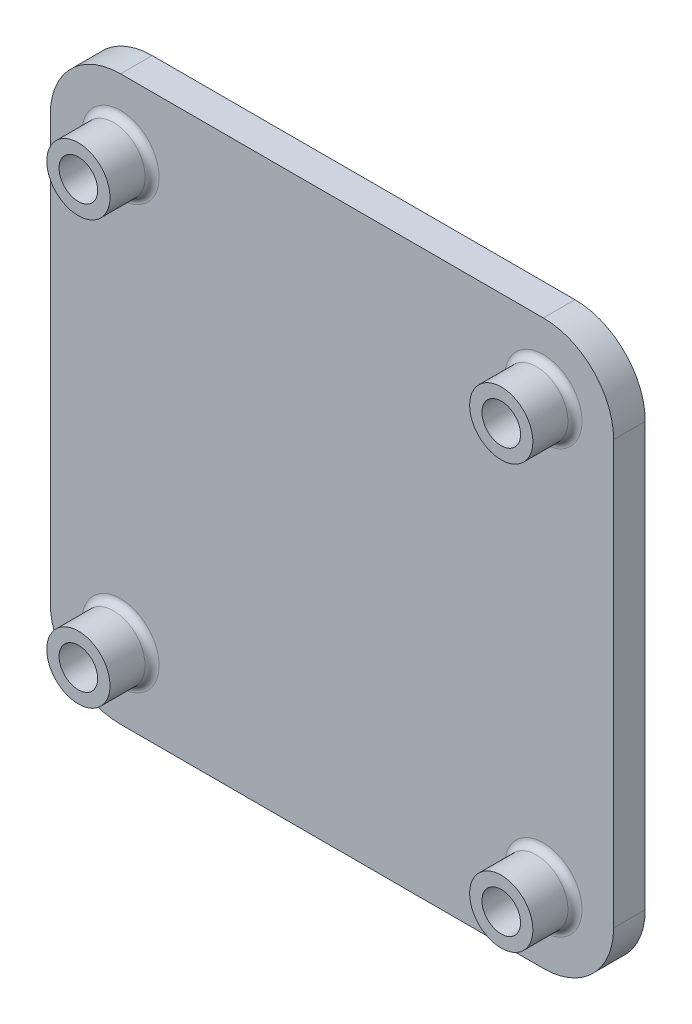
SolidWorks part; units mm, degrees
ref_plane "Front Plane" through (0, 0, 0) normal (0, 0, 1) x (1, 0, 0)
ref_plane "Top Plane" through (0, 0, 0) normal (0, 1, 0) x (1, 0, 0)
ref_plane "Right Plane" through (0, 0, 0) normal (1, 0, 0) x (0, 0, -1)
sketch "Sketch1" plane through (0, 0, 0) normal (0, 0, 1) x (1, 0, 0)
  line L0 (-30.1, 0) -> (30.1, 0) construction
  line L1 (-40.1, -40.1) -> (40.1, -40.1)
  line L2 (-40.1, -40.1) -> (-40.1, 40.1)
  line L3 (-40.1, 40.1) -> (40.1, 40.1)
  line L4 (40.1, -40.1) -> (40.1, 40.1)
  line L5 (-40.1, -40.1) -> (40.1, 40.1) construction
  line L6 (-40.1, 40.1) -> (40.1, -40.1) construction
  line L7 (55, 0) -> (-55, 0) construction
  line L8 (-30.1, -30.1) -> (-30.1, 30.1) construction
  line L9 (30.1, -30.1) -> (30.1, 30.1) construction
  point P0 (0, 0)
  point P11 (0, 0)
  point P14 (-30.1, 0)
  point P17 (30.1, 0)
  dimension "D1" = 60.2
  dimension "D2" = 60.2
  dimension "D3" = 10
  dimension "D4" = 10
extrude "Boss-Extrude1" add sketch "Sketch1" along normal blind 4.5
hole_wizard "M5 Clearance Hole1" positions "3DSketch1" profile "Sketch2" hole size "M5" standard "ANSI Metric" end condition through all
sketch3d "3DSketch1"
  line L0 (-40.1, -40.1, 0) -> (40.1, 40.1, 0) construction
  point P0 (30.1, 30.1, 0)
  point P3 (-30.1, 30.1, 0)
  point P6 (-30.1, -30.1, 0)
  point P10 (30.1, -30.1, 0)
  point P14 (30.1, 30.1, 0)
  point P16 (-30.1, 30.1, 0)
  point P18 (30.1, -30.1, 0)
  point P20 (-30.1, -30.1, 0)
sketch "Sketch2" plane through (-30.1, -30.1, 0) normal (1, 0, 0) x (0, 1, 0)
  line L0 (0, 0) -> (0, 4.5)
  line L1 (0, 4.5) -> (2.75, 4.5)
  line L2 (2.75, 4.5) -> (2.75, 0)
  line L5 (2.75, 0) -> (0, 0)
  line L11 (0, -6.35) -> (0, 107.95) construction
  dimension "Thru Hole Dia." = 5.5
  dimension "Thru Hole Depth" = 4.5
fillet "Fillet2" radius 10 4 edges at (40.1, -40.1, 2.25) (-40.1, -40.1, 2.25) (-40.1, 40.1, 2.25) (40.1, 40.1, 2.25)
sketch "Sketch3" plane through (0, 0, 4.5) normal (0, 0, 1) x (1, 0, 0)
  circle A0 centre (-30.1, 30.1) radius 4.5
  dimension "D1" = 9
extrude "Boss-Extrude2" add sketch "Sketch3" along normal blind 6
sketch "Sketch5" plane through (0, 0, 4.5) normal (0, 0, -1) x (-1, 0, 0)
  circle A1 centre (30.1, 30.1) radius 2.75
  circle A2 centre (30.1, 30.1) radius 2.75
  dimension "D1" = 0
extrude "Cut-Extrude1" cut sketch "Sketch5" against normal up to next
mirror "Mirror2" about plane through (0, 0, 0) normal (0, 1, 0) of "Boss-Extrude2", "Cut-Extrude1" second plane through (0, 0, 0) second plane normal (1, 0, 0)
fillet "Fillet4" radius 1 4 edges at (-34.6, 30.1, 4.5) (25.6, 30.1, 4.5) (-25.6, -30.1, 4.5) (25.6, -30.1, 4.5)
